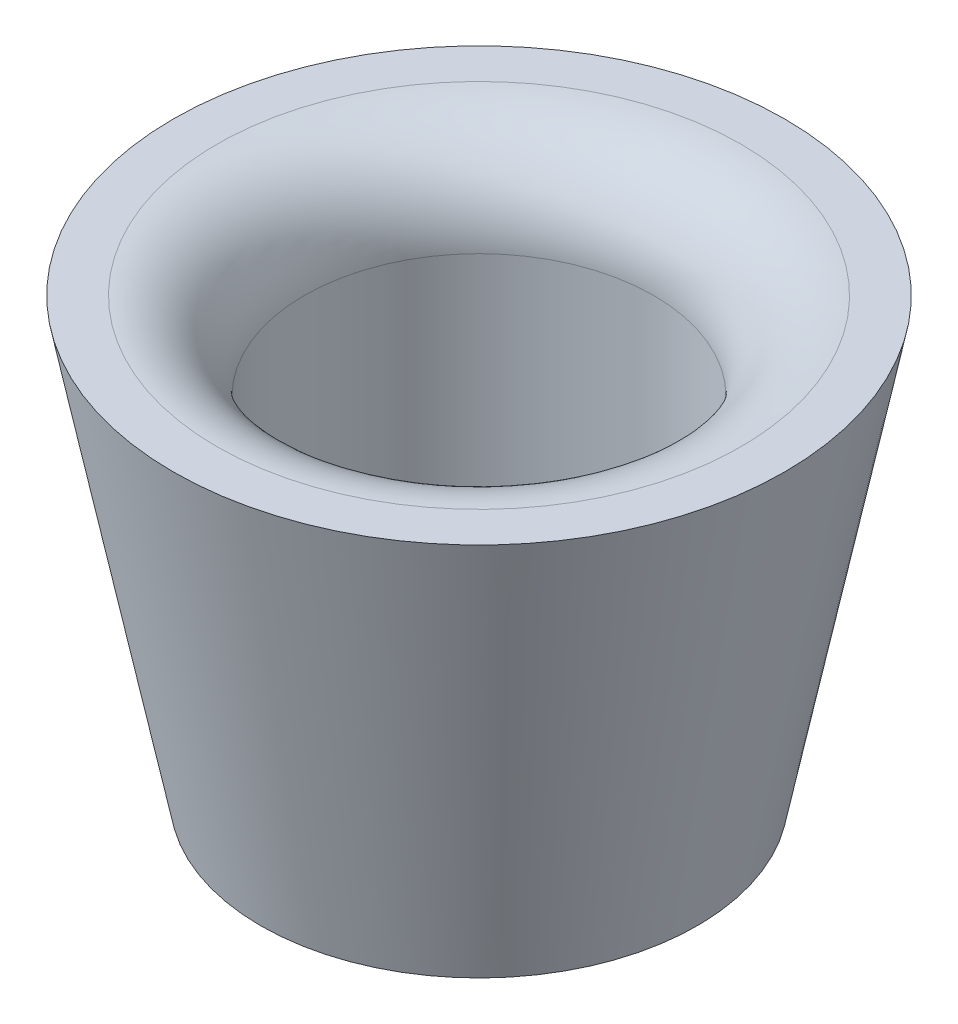
SolidWorks part; units mm, degrees
ref_plane "Front Plane" through (0, 0, 0) normal (0, 0, 1) x (1, 0, 0)
ref_plane "Top Plane" through (0, 0, 0) normal (0, 1, 0) x (1, 0, 0)
ref_plane "Right Plane" through (0, 0, 0) normal (1, 0, 0) x (0, 0, -1)
sketch "Sketch1" plane through (0, 0, 0) normal (0, 0, 1) x (1, 0, 0)
  line L0 (5, 0) -> (7, 10)
  line L4 (5, 0) -> (4, 0)
  line L5 (4, 0) -> (4, 10)
  line L6 (4, 10) -> (7, 10)
  dimension "D1" = 5
  dimension "D2" = 10
  dimension "D3" = 2
  dimension "D4" = 1
ref_axis "Axis1" through (0, 15.75, 0) along (0, -1, 0)
revolve "Revolve1" add sketch "Sketch1" angle 360 about axis through (0, 15.75, 0) along (0, -1, 0)
fillet "Fillet1" radius 2 1 edges at (0, 10, 4)
